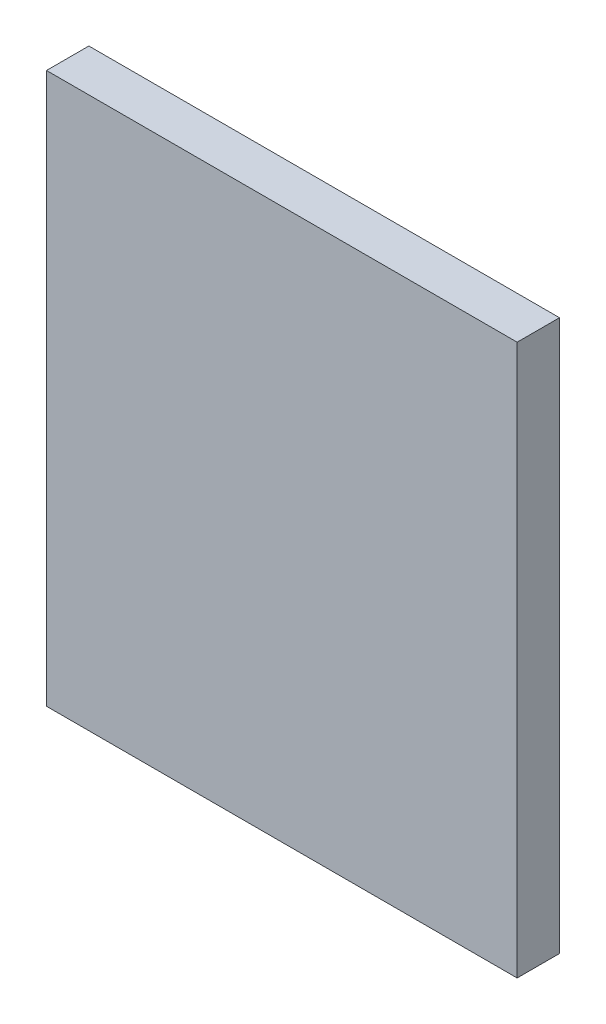
SolidWorks part; units mm, degrees
ref_plane "Front Plane" through (0, 0, 0) normal (0, 0, 1) x (1, 0, 0)
ref_plane "Top Plane" through (0, 0, 0) normal (0, 1, 0) x (1, 0, 0)
ref_plane "Right Plane" through (0, 0, 0) normal (1, 0, 0) x (0, 0, -1)
sketch "Sketch1" plane through (0, 0, 0) normal (0, 0, 1) x (1, 0, 0)
  line L1 (-100, 117) -> (100, 117)
  line L2 (-100, 117) -> (-100, -117)
  line L3 (-100, -117) -> (100, -117)
  line L4 (100, 117) -> (100, -117)
  line L5 (-100, 117) -> (100, -117) construction
  line L6 (-100, -117) -> (100, 117) construction
  point P0 (0, 0)
  dimension "D1" = 234
  dimension "D2" = 200
extrude "Boss-Extrude1" add sketch "Sketch1" along normal blind 18
sketch "Sketch2" plane through (0, 117, 0) normal (0, 1, 0) x (1, 0, 0)
  line L1 (-100, -18) -> (-82, -18)
  line L2 (-100, -18) -> (-100, -16)
  line L3 (-100, -16) -> (-82, -16)
  line L4 (-82, -18) -> (-82, -16)
  line L5 (100, -18) -> (82, -18)
  line L6 (100, -18) -> (100, -16)
  line L7 (100, -16) -> (82, -16)
  line L8 (82, -18) -> (82, -16)
  dimension "D1" = 18
  dimension "D2" = 2
  dimension "D3" = 18
  dimension "D4" = 2
